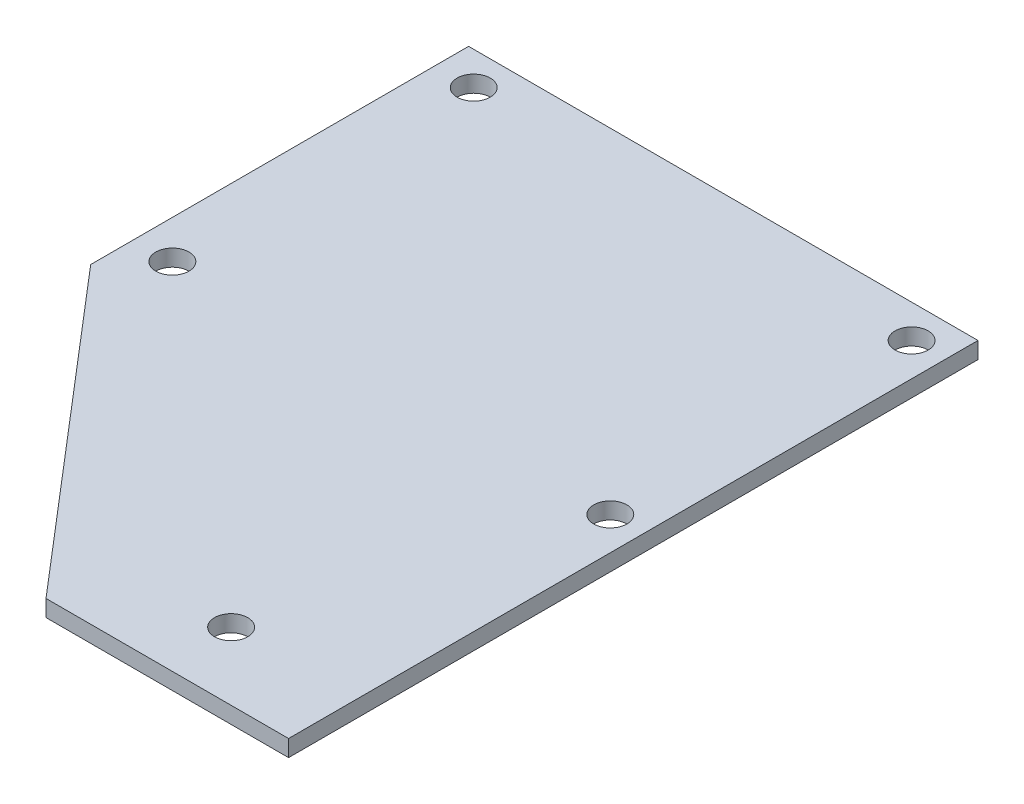
SolidWorks part; units mm, degrees
ref_plane "Front Plane" through (0, 0, 0) normal (0, 0, 1) x (1, 0, 0)
ref_plane "Top Plane" through (0, 0, 0) normal (0, 1, 0) x (1, 0, 0)
ref_plane "Right Plane" through (0, 0, 0) normal (1, 0, 0) x (0, 0, -1)
sketch "Sketch1" plane through (0, 0, 0) normal (0, 1, 0) x (1, 0, 0)
  line L0 (0, 0) -> (-48.26, 0)
  line L1 (0, 0) -> (0, 137.16)
  line L2 (0, 137.16) -> (-101.346, 137.16)
  line L3 (-101.346, 137.16) -> (-101.346, 61.976)
  line L4 (-48.26, 0) -> (-101.346, 61.976)
extrude "Boss-Extrude1" add sketch "Sketch1" along normal blind 3.302
sketch "Sketch2" plane through (0, 3.302, 0) normal (0, 1, 0) x (1, 0, 0)
  line L9 (0, 0) -> (0, 137.16) construction
  circle A2 centre (-93.726, 70.612) radius 3.302
  circle A3 centre (-24.892, 13.462) radius 3.302
  circle A4 centre (-6.604, 70.612) radius 3.302
  circle A5 centre (-6.604, 130.556) radius 3.302
  circle A6 centre (-93.726, 130.556) radius 3.302
  point P0 (-24.892, 13.462)
  point P1 (-93.726, 70.612)
  point P2 (-6.604, 70.612)
  point P3 (-6.604, 130.556)
  point P4 (-93.726, 130.556)
  dimension "D1" = 6.604
extrude "Cut-Extrude1" cut sketch "Sketch2" against normal blind 23.368
